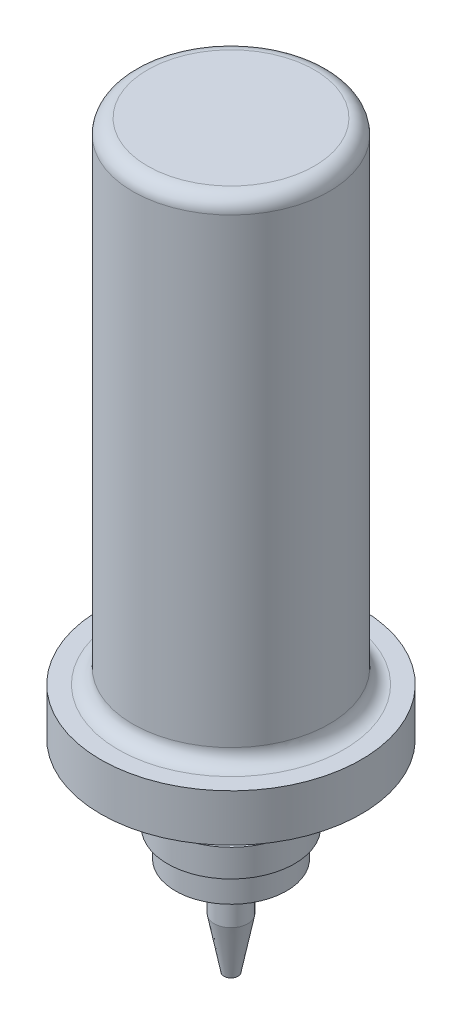
SolidWorks part; units mm, degrees
ref_plane "Front Plane" through (0, 0, 0) normal (0, 0, 1) x (1, 0, 0)
ref_plane "Top Plane" through (0, 0, 0) normal (0, 1, 0) x (1, 0, 0)
ref_plane "Right Plane" through (0, 0, 0) normal (1, 0, 0) x (0, 0, -1)
sketch "Sketch1" plane through (0, 0, 0) normal (0, 1, 0) x (1, 0, 0)
  circle A0 centre (0, 0) radius 10.0017
  dimension "D1" = 20.0035
extrude "Boss-Extrude3" add sketch "Sketch1" against normal blind 50
sketch "Sketch4" plane through (0, -50, 0) normal (0, -1, 0) x (1, 0, 0)
  circle A0 centre (0, 0) radius 13.2792
  dimension "D1" = 26.5584
extrude "Boss-Extrude4" add sketch "Sketch4" along normal blind 4.8
fillet "Fillet1" radius 1.5 2 edges at (0, 0, 10.0017) (0, -50, -10.0017)
sketch "Sketch5" plane through (0, -54.8, 0) normal (0, -1, 0) x (-1, 0, 0)
  circle A0 centre (0, 0) radius 5.291
extrude "Boss-Extrude5" add sketch "Sketch5" along normal blind 5
sketch "Sketch6" plane through (0, -59.8, 0) normal (0, -1, 0) x (-1, 0, 0)
  circle A0 centre (0, 0) radius 6.4662
extrude "Boss-Extrude6" add sketch "Sketch6" along normal blind 2.8
sketch "Sketch7" plane through (0, -62.6, 0) normal (0, -1, 0) x (-1, 0, 0)
  circle A0 centre (0, 0) radius 5.6593
extrude "Boss-Extrude7" add sketch "Sketch7" along normal blind 2.8
sketch "Sketch8" plane through (0, -65.4, 0) normal (0, -1, 0) x (1, 0, 0)
  circle A0 centre (0, 0) radius 1.7156
extrude "Boss-Extrude8" add sketch "Sketch8" along normal blind 10
chamfer "Chamfer1" distance 1 angle 79 1 edges at (0, -75.4, -1.7156)
